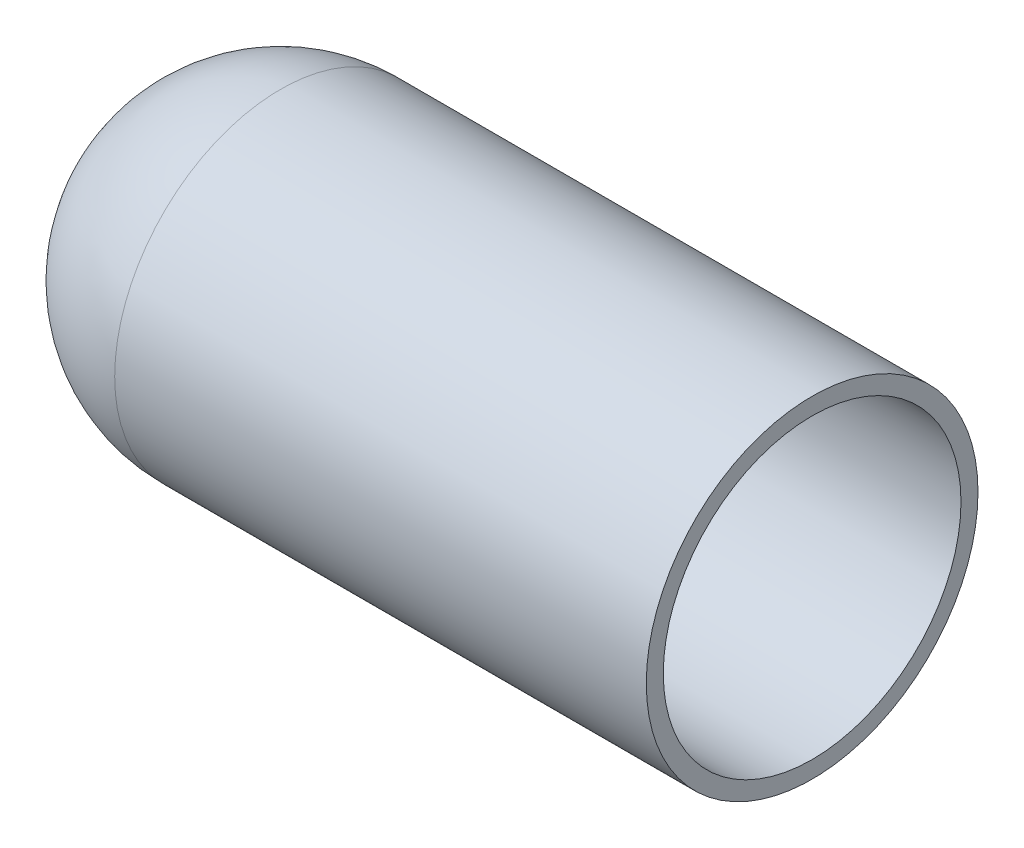
SolidWorks part; units mm, degrees
ref_plane "Front Plane" through (0, 0, 0) normal (0, 0, 1) x (1, 0, 0)
ref_plane "Top Plane" through (0, 0, 0) normal (0, 1, 0) x (1, 0, 0)
ref_plane "Right Plane" through (0, 0, 0) normal (1, 0, 0) x (0, 0, -1)
sketch "Sketch1" plane through (0, 0, 0) normal (0, 1, 0) x (1, 0, 0)
  line L0 (-16.16, 0) -> (15.09, 0) construction
  line L1 (-16.16, 9.75) -> (15.09, 9.75)
  line L3 (15.09, 9.75) -> (15.09, 0)
  line L4 (15.09, 0) -> (-25.91, 0)
  arc A0 (-16.16, 9.75) -> (-25.91, 0) centre (-16.16, 0) ccw
  point P3 (-0.535, 0)
  dimension "D2" = 9.75
  dimension "D1" = 31.25
revolve "Revolve1" add sketch "Sketch1" angle 360 about L0
shell "Shell1" thickness 1
